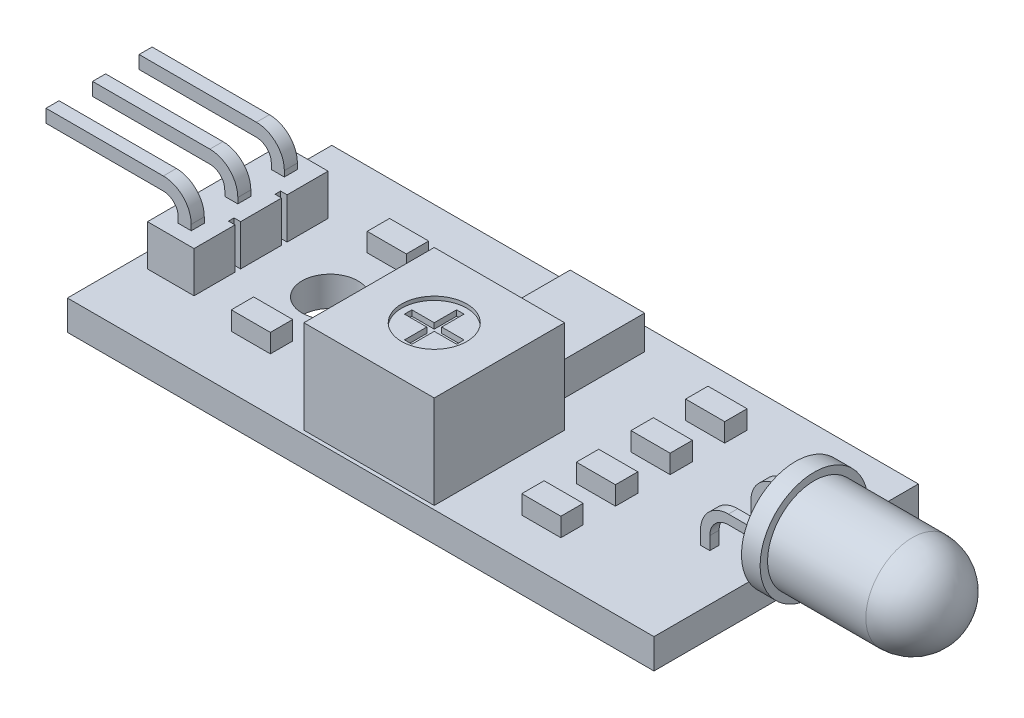
SolidWorks part; units mm, degrees
material "ABS"
ref_plane "Спереди" through (0, 0, 0) normal (0, 0, 1) x (1, 0, 0)
ref_plane "Сверху" through (0, 0, 0) normal (0, 1, 0) x (1, 0, 0)
ref_plane "Справа" through (0, 0, 0) normal (1, 0, 0) x (0, 0, -1)
sketch "Эскиз1" plane through (0, 0, 0) normal (0, 1, 0) x (1, 0, 0)
  line L0 (0, 0) -> (-18.3452, 0) construction
  line L1 (15.75, -7.1) -> (-15.75, -7.1)
  line L2 (15.75, -7.1) -> (15.75, 7.1)
  line L3 (15.75, 7.1) -> (-15.75, 7.1)
  line L4 (-15.75, -7.1) -> (-15.75, 7.1)
  line L5 (15.75, -7.1) -> (-15.75, 7.1) construction
  line L6 (15.75, 7.1) -> (-15.75, -7.1) construction
  circle A0 centre (-8.75, 0) radius 1.5
  point P0 (0, 0)
  dimension "D3" = 3
  dimension "D1" = 14.2
  dimension "D2" = 31.5
  dimension "D4" = 5.5
extrude "Бобышка-Вытянуть1" add sketch "Эскиз1" along normal blind 1.6
sketch "Эскиз2" plane through (0, 1.6, 0) normal (0, 1, 0) x (1, 0, 0)
  line L1 (-3.25, -6.9) -> (3.75, -6.9)
  line L2 (-3.25, -6.9) -> (-3.25, 0.1)
  line L3 (-3.25, 0.1) -> (3.75, 0.1)
  line L4 (3.75, -6.9) -> (3.75, 0.1)
  line L5 (-3.25, -6.9) -> (3.75, 0.1) construction
  line L6 (-3.25, 0.1) -> (3.75, -6.9) construction
  line L8 (-15.75, 7.1) -> (-15.75, -7.1) construction
  line L9 (-15.75, -7.1) -> (15.75, -7.1) construction
  point P0 (0.25, -3.4)
  dimension "D1" = 7
  dimension "D2" = 12.5
  dimension "D3" = 0.2
extrude "Бобышка-Вытянуть2" add sketch "Эскиз2" along normal blind 5
sketch "Эскиз3" plane through (0, 6.6, 0) normal (0, 1, 0) x (1, 0, 0)
  line L0 (-3.25, -3.4) -> (3.75, -3.4) construction
  line L1 (-3.25, 0.1) -> (-3.25, -6.9) construction
  line L2 (3.75, -6.9) -> (3.75, 0.1) construction
  line L3 (0.25, -3.4) -> (0.25, 5.936) construction
  circle A0 centre (0.25, -3.4) radius 1.75
  dimension "D1" = 3.5
extrude "Вырез-Вытянуть1" cut sketch "Эскиз3" against normal blind 0.2
sketch "Эскиз4" plane through (0, 6.4, 0) normal (0, 1, 0) x (1, 0, 0)
  line L0 (0.25, -3.4) -> (0.25, 6.0848) construction
  line L1 (0.25, -3.4) -> (3.05, -3.4) construction
  line L2 (0.05, -2) -> (0.45, -2)
  line L3 (0.45, -2) -> (0.45, -3.2)
  line L4 (0.45, -3.2) -> (1.65, -3.2)
  line L5 (1.65, -3.2) -> (1.65, -3.6)
  line L6 (0.45, -3.6) -> (1.65, -3.6)
  line L7 (0.45, -4.8) -> (0.45, -3.6)
  line L8 (0.05, -4.8) -> (0.45, -4.8)
  line L9 (0.05, -4.8) -> (0.05, -3.6)
  line L10 (0.05, -3.6) -> (-1.15, -3.6)
  line L11 (-1.15, -3.2) -> (-1.15, -3.6)
  line L12 (0.05, -3.2) -> (-1.15, -3.2)
  line L13 (0.05, -2) -> (0.05, -3.2)
  point P10 (1.65, -3.4)
  point P13 (-1.15, -3.4)
  point P15 (0.25, -4.8)
  point P20 (0.25, -2)
  dimension "D1" = 0.4
  dimension "D2" = 2.8
extrude "Вырез-Вытянуть2" cut sketch "Эскиз4" against normal blind 0.3
sketch "Эскиз6" plane through (0, 1.6, 0) normal (0, 1, 0) x (1, 0, 0)
  line L0 (15.75, 7.1) -> (-15.75, 7.1) construction
  line L1 (-1.75, 5.9) -> (2.25, 5.9)
  line L2 (-1.75, 5.9) -> (-1.75, 1.4)
  line L3 (-1.75, 1.4) -> (2.25, 1.4)
  line L4 (2.25, 5.9) -> (2.25, 1.4)
  line L5 (-15.75, 7.1) -> (-15.75, -7.1) construction
  dimension "D1" = 4
  dimension "D2" = 4.5
  dimension "D3" = 1.2
  dimension "D4" = 14
extrude "Бобышка-Вытянуть3" add sketch "Эскиз6" along normal blind 1.8
sketch "Эскиз7" plane through (0, 1.6, 0) normal (0, 1, 0) x (1, 0, 0)
  line L0 (-15.75, 0) -> (15.75, 0) construction
  line L1 (-15.75, 7.1) -> (-15.75, -7.1) construction
  line L2 (15.75, -7.1) -> (15.75, 7.1) construction
  line L3 (7.6, -5.2712) -> (7.6, 5.2712) construction
  line L4 (-8.75, -4.7808) -> (-8.75, 4.7808) construction
  line L5 (6.55, 2.0667) -> (8.65, 2.0667)
  line L6 (6.55, 2.0667) -> (6.55, 0.8667)
  line L7 (6.55, 0.8667) -> (8.65, 0.8667)
  line L8 (8.65, 2.0667) -> (8.65, 0.8667)
  line L9 (6.55, 2.0667) -> (8.65, 0.8667) construction
  line L10 (6.55, 0.8667) -> (8.65, 2.0667) construction
  line L11 (6.55, 5) -> (8.65, 5)
  line L12 (6.55, 5) -> (6.55, 3.8)
  line L13 (6.55, 3.8) -> (8.65, 3.8)
  line L14 (8.65, 5) -> (8.65, 3.8)
  line L15 (6.55, 5) -> (8.65, 3.8) construction
  line L16 (6.55, 3.8) -> (8.65, 5) construction
  line L17 (-5.75, -1.9) -> (-4.55, -4) construction
  line L18 (-9.8, 4.25) -> (-7.7, 4.25)
  line L19 (-9.8, 4.25) -> (-9.8, 3.05)
  line L20 (-9.8, 3.05) -> (-7.7, 3.05)
  line L21 (-7.7, 4.25) -> (-7.7, 3.05)
  line L22 (-9.8, 4.25) -> (-7.7, 3.05) construction
  line L23 (-9.8, 3.05) -> (-7.7, 4.25) construction
  line L24 (-5.75, 4) -> (-4.55, 4)
  line L25 (-5.75, 4) -> (-5.75, 1.9)
  line L26 (-5.75, 1.9) -> (-4.55, 1.9)
  line L27 (-4.55, 4) -> (-4.55, 1.9)
  line L28 (-5.75, 4) -> (-4.55, 1.9) construction
  line L29 (-5.75, 1.9) -> (-4.55, 4) construction
  line L30 (-5.75, -4) -> (-4.55, -1.9) construction
  line L31 (-9.8, -3.05) -> (-7.7, -4.25) construction
  line L32 (-9.8, -4.25) -> (-7.7, -3.05) construction
  line L33 (6.55, -3.8) -> (8.65, -5) construction
  line L34 (6.55, -5) -> (8.65, -3.8) construction
  line L35 (6.55, -0.8667) -> (8.65, -2.0667) construction
  line L36 (6.55, -2.0667) -> (8.65, -0.8667) construction
  line L37 (-4.55, -4) -> (-4.55, -1.9)
  line L38 (-5.75, -1.9) -> (-4.55, -1.9)
  line L39 (-5.75, -4) -> (-5.75, -1.9)
  line L40 (-5.75, -4) -> (-4.55, -4)
  line L41 (-7.7, -4.25) -> (-7.7, -3.05)
  line L42 (-9.8, -3.05) -> (-7.7, -3.05)
  line L43 (-9.8, -4.25) -> (-9.8, -3.05)
  line L44 (-9.8, -4.25) -> (-7.7, -4.25)
  line L45 (8.65, -5) -> (8.65, -3.8)
  line L46 (6.55, -3.8) -> (8.65, -3.8)
  line L47 (6.55, -5) -> (6.55, -3.8)
  line L48 (6.55, -5) -> (8.65, -5)
  line L49 (8.65, -2.0667) -> (8.65, -0.8667)
  line L50 (6.55, -0.8667) -> (8.65, -0.8667)
  line L51 (6.55, -2.0667) -> (6.55, -0.8667)
  line L52 (6.55, -2.0667) -> (8.65, -2.0667)
  line L53 (6.55, 3.8) -> (6.55, 2.0667) construction
  line L54 (6.55, 0.8667) -> (6.55, -0.8667) construction
  point P6 (-5.15, -2.95)
  point P8 (7.6, 1.4667)
  point P13 (7.6, 4.4)
  point P21 (-8.75, 3.65)
  point P26 (-5.15, 2.95)
  point P48 (-8.75, 0)
  point P49 (7.6, 0)
  point P50 (-8.75, -3.65)
  point P51 (7.6, -4.4)
  point P52 (7.6, -1.4667)
  dimension "D1" = 2.1
  dimension "D2" = 1.2
  dimension "D3" = 10
  dimension "D4" = 7.1
  dimension "D5" = 8
  dimension "D6" = 8.5
  dimension "D7" = 10
extrude "Бобышка-Вытянуть4" add sketch "Эскиз7" along normal blind 1
sketch "Эскиз9" plane through (0, 0, 0) normal (0, 0, 1) x (1, 0, 0)
  line L0 (12.75, 2.3) -> (12.75, -0.5)
  line L1 (12.75, -0.5) -> (13.25, -0.5)
  line L2 (13.25, -0.5) -> (13.25, 2.3)
  line L3 (14.25, 3.3) -> (16.25, 3.3)
  line L4 (16.25, 3.3) -> (16.25, 3.8)
  line L5 (16.25, 3.8) -> (14.25, 3.8)
  line L6 (-15.75, 0) -> (15.75, 0) construction
  line L7 (15.75, 1.6) -> (15.75, 0) construction
  line L8 (-15.75, 1.6) -> (15.75, 1.6) construction
  arc A0 (13.25, 2.3) -> (14.25, 3.3) centre (14.25, 2.3) cw
  arc A1 (12.75, 2.3) -> (14.25, 3.8) centre (14.25, 2.3) cw
  dimension "D6" = 1
  dimension "D7" = 1.5
  dimension "D1" = 0.5
  dimension "D2" = 0.5
  dimension "D3" = 2.5
  dimension "D4" = 2.2
  dimension "D5" = 0.5
extrude "Бобышка-Вытянуть5" add sketch "Эскиз9" against normal blind 0.5 from offset 1.6
pattern_linear "Линейный массив1" count 2 spacing 2.7 along (0, 0, -1) of "Бобышка-Вытянуть5"
sketch "Эскиз10" plane through (0, 0, 0) normal (0, 0, 1) x (1, 0, 0)
  line L0 (16.25, 3.55) -> (22.5604, 3.55) construction
  line L1 (16.25, 3.3) -> (16.25, 3.8) construction
  line L2 (16.25, 3.55) -> (16.25, 6.45)
  line L3 (16.25, 6.45) -> (17.25, 6.45)
  line L4 (17.25, 6.45) -> (17.25, 6.05)
  line L5 (17.25, 6.05) -> (22.53, 6.05)
  line L6 (16.25, 3.55) -> (25.03, 3.55)
  arc A0 (25.03, 3.55) -> (22.53, 6.05) centre (22.53, 3.55) ccw
  dimension "D1" = 5.8
  dimension "D2" = 5
  dimension "D3" = 1
  dimension "D4" = 8.78
revolve "Повернуть1" add sketch "Эскиз10" angle 360 about L0
sketch "Эскиз11" plane through (0, 0, 0) normal (0, 0, 1) x (1, 0, 0)
  line L0 (-13.35, -0.5) -> (-14.05, -0.5)
  line L1 (-14.05, -0.5) -> (-14.05, 4.1)
  line L2 (-14.85, 4.9) -> (-21.15, 4.9)
  line L3 (-21.15, 4.9) -> (-21.15, 5.6)
  line L4 (-21.15, 5.6) -> (-14.85, 5.6)
  line L5 (-13.35, 4.1) -> (-13.35, -0.5)
  line L6 (12.75, -0.5) -> (13.25, -0.5) construction
  line L7 (-15.75, 1.6) -> (-15.75, 0) construction
  line L8 (-15.75, 1.6) -> (15.75, 1.6) construction
  arc A0 (-14.85, 5.6) -> (-13.35, 4.1) centre (-14.85, 4.1) cw
  arc A1 (-14.05, 4.1) -> (-14.85, 4.9) centre (-14.85, 4.1) ccw
  dimension "D5" = 1.5
  dimension "D6" = 0.8
  dimension "D1" = 0.7
  dimension "D2" = 7.8
  dimension "D3" = 5.4
  dimension "D4" = 4
extrude "Бобышка-Вытянуть6" add sketch "Эскиз11" along normal mid plane 0.7
pattern_linear "Линейный массив2" count 2 spacing 2.5 along (0, 0, 1) of "Бобышка-Вытянуть6"
pattern_linear "Линейный массив3" count 2 spacing 2.5 along (0, 0, -1) of "Бобышка-Вытянуть6"
sketch "Эскиз12" plane through (0, 1.6, 0) normal (0, 1, 0) x (1, 0, 0)
  line L0 (-14.05, 0) -> (-13.35, 0) construction
  line L1 (-14.05, -0.35) -> (-14.05, 0.35) construction
  line L2 (-13.35, 0.35) -> (-13.35, -0.35) construction
  line L3 (-14.05, 2.5) -> (-13.35, 2.5) construction
  line L4 (-14.05, 2.15) -> (-14.05, 2.85) construction
  line L5 (-13.35, 2.85) -> (-13.35, 2.15) construction
  line L6 (-14.05, -2.5) -> (-13.35, -2.5) construction
  line L7 (-14.05, -2.85) -> (-14.05, -2.15) construction
  line L8 (-13.35, -2.15) -> (-13.35, -2.85) construction
  line L9 (-14.6, 1.4) -> (-14.6, 1.1)
  line L10 (-12.45, -1.4) -> (-14.95, -1.4)
  line L11 (-12.45, -1.4) -> (-12.45, -3.6)
  line L12 (-12.45, -3.6) -> (-14.95, -3.6)
  line L13 (-14.95, -1.4) -> (-14.95, -3.6)
  line L14 (-12.45, -1.4) -> (-14.95, -3.6) construction
  line L15 (-12.45, -3.6) -> (-14.95, -1.4) construction
  line L16 (-14.95, 1.1) -> (-12.45, 1.1)
  line L17 (-14.95, 1.1) -> (-14.95, -1.1)
  line L18 (-14.95, -1.1) -> (-12.45, -1.1)
  line L19 (-12.45, 1.1) -> (-12.45, -1.1)
  line L20 (-14.95, 1.1) -> (-12.45, -1.1) construction
  line L21 (-14.95, -1.1) -> (-12.45, 1.1) construction
  line L22 (-14.95, 3.6) -> (-12.45, 3.6)
  line L23 (-14.95, 3.6) -> (-14.95, 1.4)
  line L24 (-14.95, 1.4) -> (-12.45, 1.4)
  line L25 (-12.45, 3.6) -> (-12.45, 1.4)
  line L26 (-14.95, 3.6) -> (-12.45, 1.4) construction
  line L27 (-14.95, 1.4) -> (-12.45, 3.6) construction
  line L28 (-14.6, -1.1) -> (-14.6, -1.4)
  line L29 (-13.7, 0) -> (-13.7, 4.664) construction
  line L30 (-12.8, -1.1) -> (-12.8, -1.4)
  line L31 (-12.8, 1.4) -> (-12.8, 1.1)
  point P18 (-13.7, -2.5)
  point P23 (-13.7, 0)
  point P28 (-13.7, 2.5)
  dimension "D1" = 2.5
  dimension "D2" = 7.2
  dimension "D3" = 1.8
extrude "Бобышка-Вытянуть7" add sketch "Эскиз12" along normal blind 2.2 contours L25 L22 L23 L24 | L31 L24 L9 L16 | L19 L16 L17 L18 | L30 L18 L28 L10 | L10 L13 L12 L11
sketch "Эскиз13" plane through (0, 0, 0) normal (0, -1, 0) x (1, 0, 0)
  line L0 (0.25, -0.1) -> (0.25, 8.1547) construction
  line L1 (3.75, -0.1) -> (-3.25, -0.1) construction
  line L3 (-15.75, 7.1) -> (15.75, 7.1) construction
  circle A0 centre (-2.25, 3.6) radius 0.4
  circle A1 centre (0.25, 1.1) radius 0.4
  circle A2 centre (2.75, 3.6) radius 0.4
  dimension "D1" = 0.8
  dimension "D3" = 5
  dimension "D2" = 3.5
  dimension "D4" = 6
extrude "Бобышка-Вытянуть8" add sketch "Эскиз13" along normal up to surface (0.5 mm away) up to face at (13, -0.5, 1.35)
